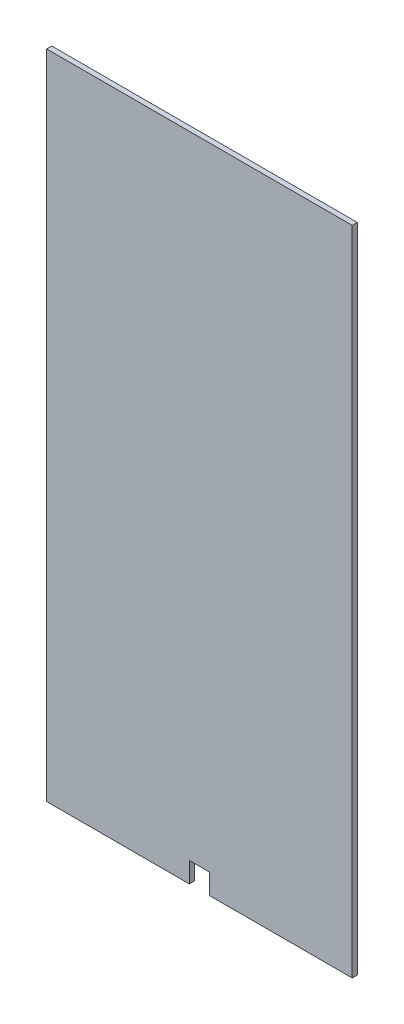
SolidWorks part; units mm, degrees
ref_plane "Ebene vorne" through (0, 0, 0) normal (0, 0, 1) x (1, 0, 0)
ref_plane "Ebene oben" through (0, 0, 0) normal (0, 1, 0) x (1, 0, 0)
ref_plane "Ebene rechts" through (0, 0, 0) normal (1, 0, 0) x (0, 0, -1)
sketch "Skizze1" plane through (0, 0, 0) normal (0, 0, 1) x (1, 0, 0)
  line L0 (0, 906.9525) -> (0, -268.3571) construction
  line L1 (-416.5857, 0) -> (416.3192, 0) construction
  line L2 (20, 40) -> (-20, 40)
  line L3 (-20, 40) -> (-20, 0)
  line L4 (-20, 0) -> (-300, 0)
  line L5 (-300, 0) -> (-300, 1280)
  line L6 (-300, 1280) -> (300, 1280)
  line L7 (300, 0) -> (300, 1280)
  line L8 (20, 0) -> (300, 0)
  line L9 (20, 40) -> (20, 0)
  point P12 (0, 1280)
  point P15 (0, 40)
  dimension "D1" = 600
  dimension "D2" = 1280
  dimension "D3" = 40
  dimension "D4" = 40
extrude "Aufsatz-Linear austragen1" add sketch "Skizze1" along normal blind 10
